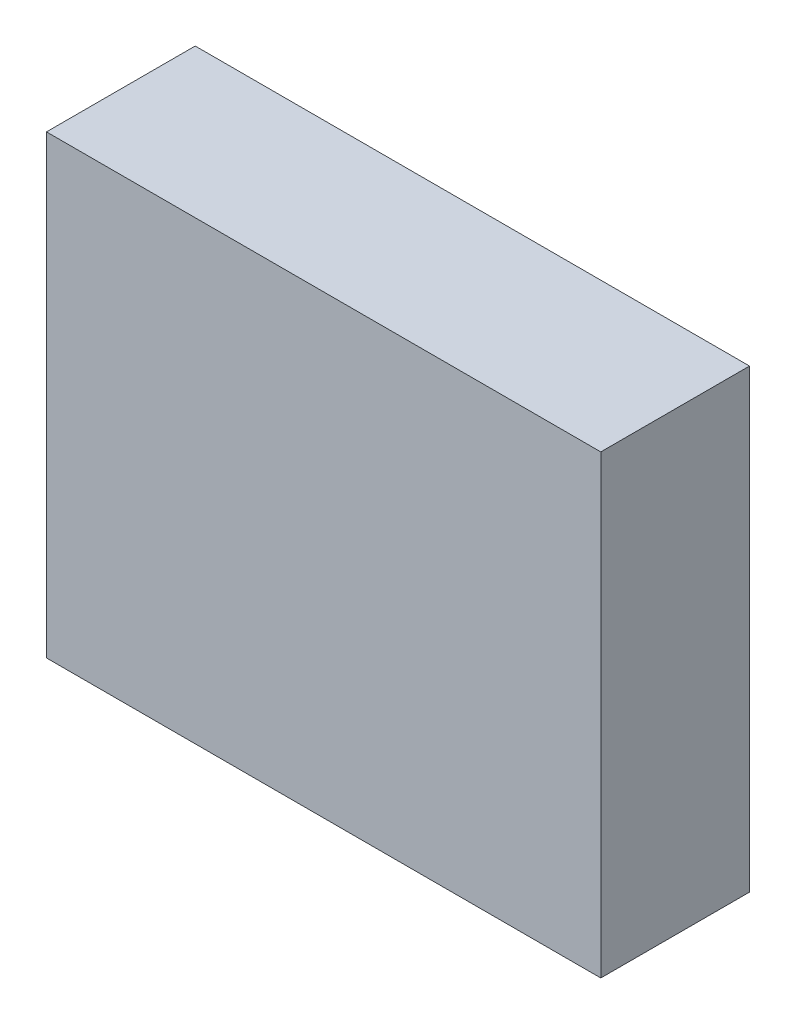
SolidWorks part; units mm, degrees
ref_plane "Front Plane" through (0, 0, 0) normal (0, 0, 1) x (1, 0, 0)
ref_plane "Top Plane" through (0, 0, 0) normal (0, 1, 0) x (1, 0, 0)
ref_plane "Right Plane" through (0, 0, 0) normal (1, 0, 0) x (0, 0, -1)
sketch "Sketch1" plane through (0, 0, 0) normal (0, 0, 1) x (1, 0, 0)
  line L0 (-1.8635, 1.5635) -> (1.8635, 1.5635)
  line L1 (1.8635, 1.5635) -> (1.8635, -1.5)
  line L2 (1.8635, -1.5) -> (-1.8635, -1.5)
  line L3 (-1.8635, -1.5) -> (-1.8635, 1.5635)
extrude "Component_Outline" add sketch "Sketch1" along normal blind 1 separate body
sketch3d "3DSketch1"
  line L0 (0, 0, 0) -> (1, 0, 0)
  line L1 (0, 0, 0) -> (0, 1, 0)
  line L2 (0, 0, 0) -> (0, 0, 1)
  point P0 (0, 0, 0)
